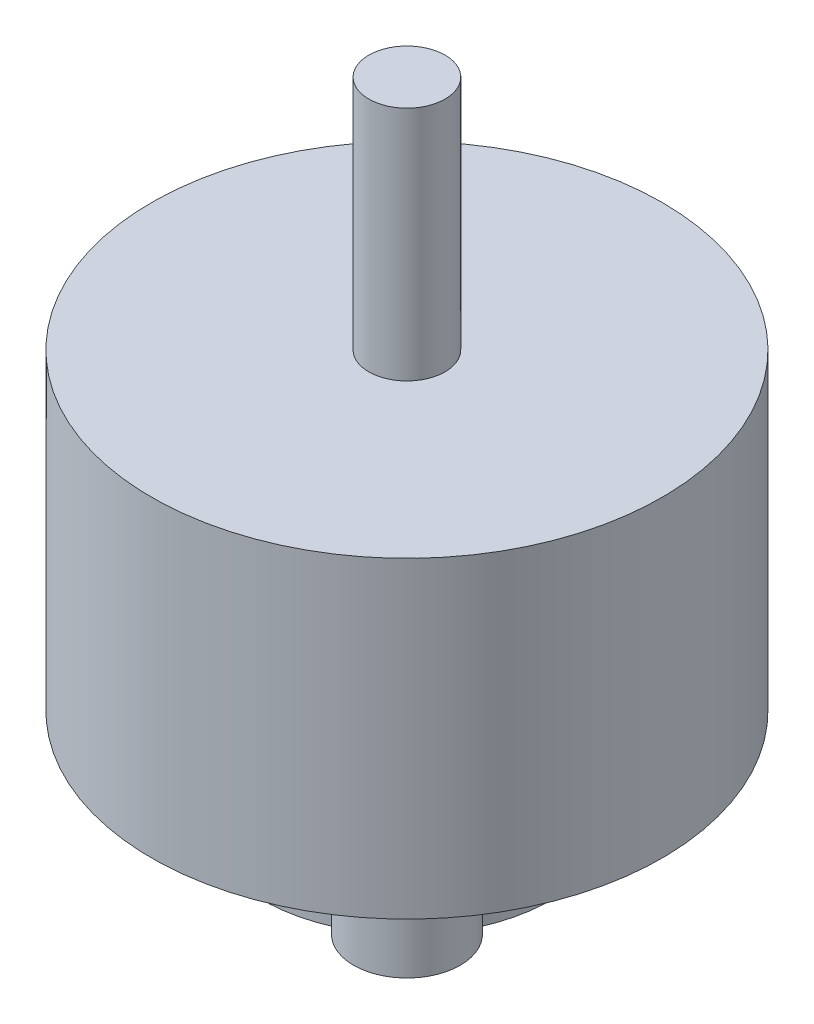
SolidWorks part; units mm, degrees
ref_plane "Plan de face" through (0, 0, 0) normal (0, 0, 1) x (1, 0, 0)
ref_plane "Plan de dessus" through (0, 0, 0) normal (0, 1, 0) x (1, 0, 0)
ref_plane "Plan de droite" through (0, 0, 0) normal (1, 0, 0) x (0, 0, -1)
sketch "Esquisse1" plane through (0, 0, 0) normal (0, 0, 1) x (1, 0, 0)
  line L0 (0, 0) -> (0, 42) construction
  line L1 (0, 0) -> (-9.5, 0)
  line L2 (-9.5, 0) -> (-9.5, 3.5)
  line L3 (-9.5, 3.5) -> (-7.5, 3.5)
  line L4 (-7.5, 3.5) -> (-6.75, 6)
  line L5 (-6.75, 6) -> (-16.75, 6)
  line L6 (-16.75, 6) -> (-16.75, 26.5)
  line L7 (-16.75, 26.5) -> (-2.5, 26.5)
  line L8 (-2.5, 26.5) -> (-2.5, 42)
  line L9 (-2.5, 42) -> (0, 42)
  line L10 (0, 0) -> (0, 42)
  dimension "D1" = 42
  dimension "D2" = 33.5
  dimension "D3" = 5
  dimension "D4" = 19
  dimension "D5" = 2
  dimension "D6" = 20.5
  dimension "D7" = 3.5
  dimension "D8" = 2.5
  dimension "D9" = 10
revolve "Révolution1" add sketch "Esquisse1" angle 360 about L0
sketch "Esquisse2" plane through (0, 0, 0) normal (0, -1, 0) x (-1, 0, 0)
  line L0 (0, 0) -> (0, -9.5) construction
  line L1 (6.7175, -6.7175) -> (0, 0) construction
  line L2 (0, 0) -> (6.7175, -6.7175) construction
  line L3 (0, 0) -> (-6.7175, -6.7175) construction
  circle A0 centre (6.7175, -6.7175) radius 3.5
  circle A1 centre (0, 0) radius 9.5 construction
  circle A2 centre (-6.7175, -6.7175) radius 3.5
  circle A3 centre (-6.7175, 6.7175) radius 3.5
  circle A4 centre (6.7175, 6.7175) radius 3.5
  dimension "D1" = 7
  dimension "D2" = 45
  dimension "D4" = 90
  dimension "D5" = 9.5
  dimension "D3" = 4
extrude "Boss.-Extru.1" add sketch "Esquisse2" against normal up to surface (3.5 mm away) up to face at (0, 3.5, -9.5)
hole_wizard "Dégagement M31" positions "Esquisse3D1" profile "Esquisse3" hole size "M3" standard "ISO"
sketch3d "Esquisse3D1"
  line L0 (0, 0, 0) -> (0, 0, 9.5) construction
  line L2 (-6.7175, 0, 6.7175) -> (0, 0, 0) construction
  line L4 (6.7175, 0, 6.7175) -> (0, 0, 0) construction
  line L6 (6.7175, 0, -6.7175) -> (0, 0, 0) construction
  line L8 (0, 0, 0) -> (-6.7175, 0, -6.7175) construction
  circle A2 centre (0, 0, 0) radius 9.5
  point P0 (-6.7175, 0, 6.7175)
  point P2 (6.7175, 0, 6.7175)
  point P4 (6.7175, 0, -6.7175)
  point P6 (-6.7175, 0, -6.7175)
  point P17 (0, 9.5, 0)
  dimension "D1" = 19
  dimension "D2" = 45
  dimension "D3" = 45
  dimension "D4" = 90
  dimension "D5" = 90
sketch "Esquisse3" plane through (-6.7175, 0, 6.7175) normal (1, 0, 0) x (0, 0, -1)
  line L0 (0, 0) -> (0, 3.5)
  line L1 (0, 3.5) -> (1.7, 3.5)
  line L2 (1.7, 3.5) -> (1.7, 0)
  line L5 (1.7, 0) -> (0, 0)
  line L11 (0, -6.35) -> (0, 107.95) construction
  dimension "Diamètre du perçage jusqu'au prochain" = 3.4
  dimension "Profondeur du perçage jusqu'au prochain" = 3.5
